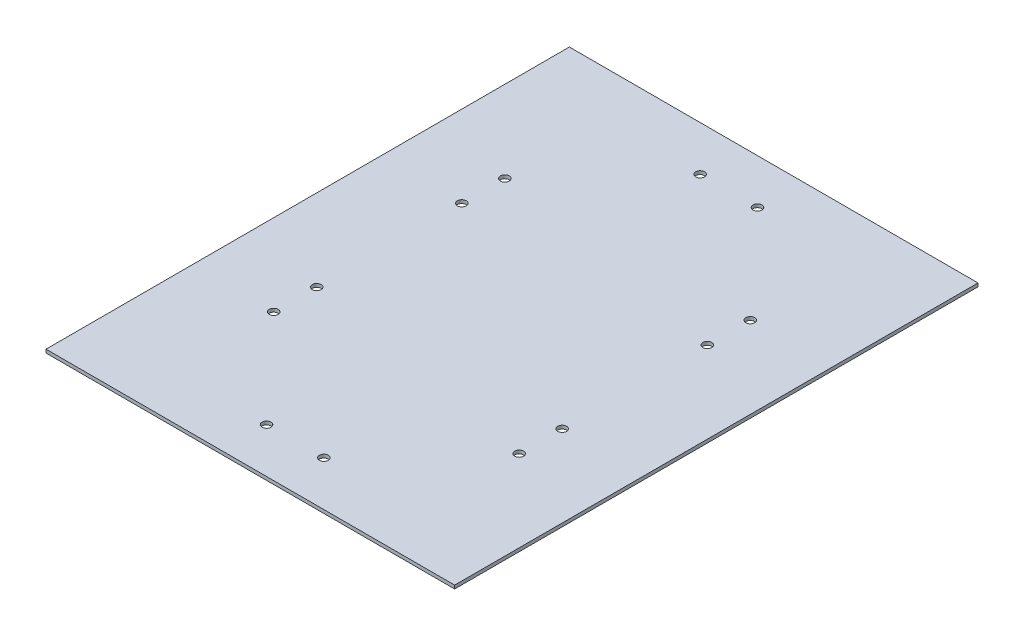
SolidWorks part; units mm, degrees
ref_plane "Front Plane" through (0, 0, 0) normal (0, 0, 1) x (1, 0, 0)
ref_plane "Top Plane" through (0, 0, 0) normal (0, 1, 0) x (1, 0, 0)
ref_plane "Right Plane" through (0, 0, 0) normal (1, 0, 0) x (0, 0, -1)
sketch "Sketch1" plane through (0, 0, 0) normal (0, 1, 0) x (1, 0, 0)
  line L0 (0, 0) -> (0, 221.2322) construction
  line L1 (-180.975, -231.775) -> (180.975, -231.775)
  line L2 (-180.975, -231.775) -> (-180.975, 231.775)
  line L3 (-180.975, 231.775) -> (180.975, 231.775)
  line L4 (180.975, -231.775) -> (180.975, 231.775)
  line L5 (-180.975, -231.775) -> (180.975, 231.775) construction
  line L6 (-180.975, 231.775) -> (180.975, -231.775) construction
  line L7 (-89.662, -166.624) -> (89.662, -166.624) construction
  line L8 (-89.662, -166.624) -> (-89.662, 166.624) construction
  line L9 (-89.662, 166.624) -> (89.662, 166.624) construction
  line L10 (89.662, -166.624) -> (89.662, 166.624) construction
  line L11 (0, 0) -> (-157.1667, 0) construction
  circle A0 centre (-108.712, 64.262) radius 3.937
  circle A1 centre (-108.712, 102.362) radius 3.937
  circle A2 centre (-108.712, -102.362) radius 3.937
  circle A3 centre (-108.712, -64.262) radius 3.937
  circle A4 centre (-25.4, 192.024) radius 3.937
  circle A5 centre (-25.4, -192.024) radius 3.937
  circle A6 centre (25.4, -192.024) radius 3.937
  circle A7 centre (108.712, -64.262) radius 3.937
  circle A8 centre (108.712, -102.362) radius 3.937
  circle A9 centre (25.4, 192.024) radius 3.937
  circle A10 centre (108.712, 102.362) radius 3.937
  circle A11 centre (108.712, 64.262) radius 3.937
  point P0 (180.975, 231.775)
  point P1 (0, 0)
  point P5 (89.662, 166.624)
  point P7 (-89.662, -166.624)
extrude "Boss-Extrude1" add sketch "Sketch1" along normal blind 3
